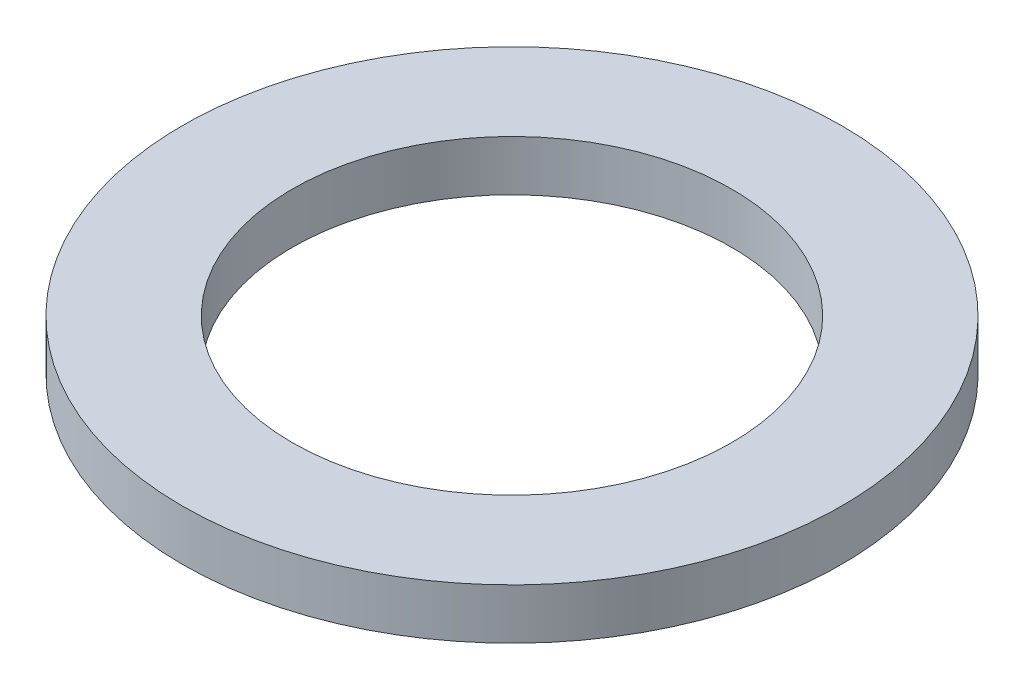
SolidWorks part; units mm, degrees
material "PMMA"
ref_plane "Plan de face" through (0, 0, 0) normal (0, 0, 1) x (1, 0, 0)
ref_plane "Plan de dessus" through (0, 0, 0) normal (0, 1, 0) x (1, 0, 0)
ref_plane "Plan de droite" through (0, 0, 0) normal (1, 0, 0) x (0, 0, -1)
sketch "Esquisse1" plane through (0, 0, 0) normal (0, 1, 0) x (1, 0, 0)
  circle A0 centre (0, 0) radius 15
  circle A1 centre (0, 0) radius 10
  dimension "D1" = 20
  dimension "D2" = 30
extrude "Boss.-Extru.1" add sketch "Esquisse1" along normal blind 2.3
